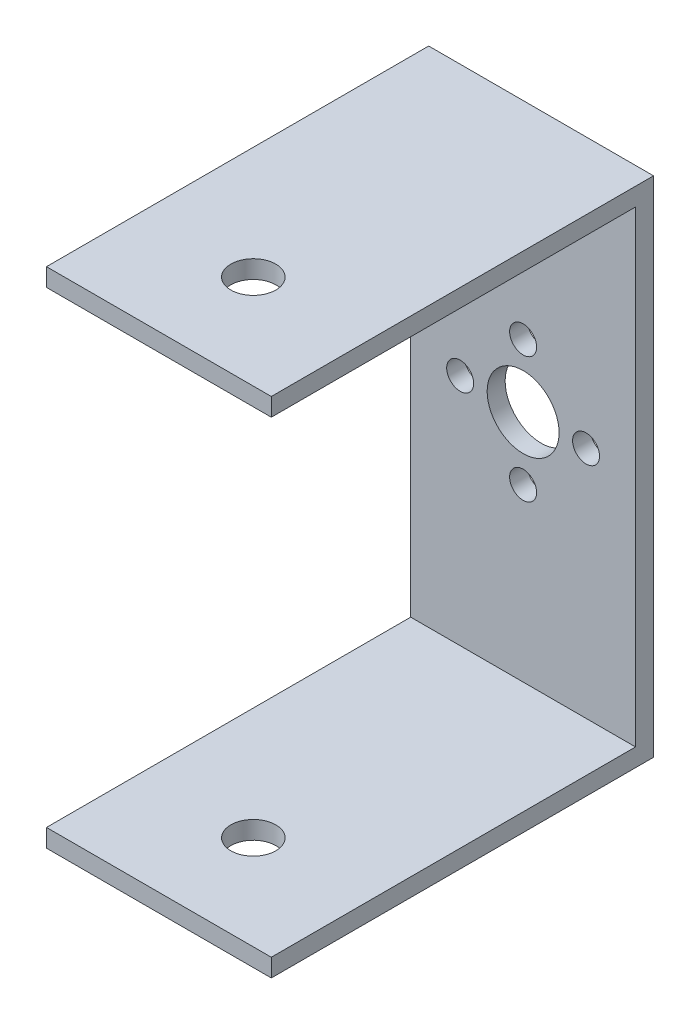
SolidWorks part; units mm, degrees
ref_plane "Front Plane" through (0, 0, 0) normal (0, 0, 1) x (1, 0, 0)
ref_plane "Top Plane" through (0, 0, 0) normal (0, 1, 0) x (1, 0, 0)
ref_plane "Right Plane" through (0, 0, 0) normal (1, 0, 0) x (0, 0, -1)
sketch "Sketch1" plane through (0, 0, 0) normal (0, 0, 1) x (1, 0, 0)
  line L1 (-12.6748, 30.5029) -> (12.3252, 30.5029)
  line L2 (-12.6748, 30.5029) -> (-12.6748, -21.4971)
  line L3 (-12.6748, -21.4971) -> (12.3252, -21.4971)
  line L4 (12.3252, 30.5029) -> (12.3252, -21.4971)
  dimension "D1" = 25
  dimension "D2" = 52
extrude "Boss-Extrude1" add sketch "Sketch1" along normal blind 2
sketch "Sketch2" plane through (0, 30.5029, 0) normal (0, 1, 0) x (1, 0, 0)
  line L1 (-12.6748, 0) -> (12.3252, 0)
  line L2 (-12.6748, 0) -> (-12.6748, -42.5)
  line L3 (-12.6748, -42.5) -> (12.3252, -42.5)
  line L4 (12.3252, 0) -> (12.3252, -42.5)
  dimension "D1" = 25
  dimension "D2" = 42.5
extrude "Boss-Extrude2" add sketch "Sketch2" along normal blind 2
sketch "Sketch3" plane through (0, -21.4971, 0) normal (0, -1, 0) x (-1, 0, 0)
  line L1 (-12.3252, 0) -> (12.6748, 0)
  line L2 (-12.3252, 0) -> (-12.3252, -42.5)
  line L3 (-12.3252, -42.5) -> (12.6748, -42.5)
  line L4 (12.6748, 0) -> (12.6748, -42.5)
  dimension "D1" = 25
  dimension "D2" = 42.5
extrude "Boss-Extrude3" add sketch "Sketch3" along normal blind 2
sketch "Sketch4" plane through (0, 32.5029, 0) normal (0, 1, 0) x (1, 0, 0)
  line L0 (-12.6748, 0) -> (-12.6748, -42.5) construction
  line L1 (12.3252, 0) -> (-12.6748, 0) construction
  circle A0 centre (-0.1748, -32) radius 2.5
  dimension "D1" = 12.5
  dimension "D2" = 32
extrude "Cut-Extrude1" cut sketch "Sketch4" against normal blind 70
sketch "Sketch5" plane through (0, 0, 0) normal (0, 0, -1) x (-1, 0, 0)
  line L0 (12.6748, 32.5029) -> (12.6748, -23.4971) construction
  circle A0 centre (0.1748, 4.5029) radius 4
  dimension "D1" = 12.5
extrude "Cut-Extrude2" cut sketch "Sketch5" against normal blind 21
sketch "Sketch6" plane through (0, 0, 0) normal (0, 0, -1) x (-1, 0, 0)
  circle A0 centre (7.1748, 4.5029) radius 1.5
  circle A1 centre (0.1748, 4.5029) radius 4 construction
  circle A2 centre (0.1748, -2.4971) radius 1.5
  circle A3 centre (-6.8252, 4.5029) radius 1.5
  circle A4 centre (0.1748, 11.5029) radius 1.5
  point P13 (0.1748, 4.5029)
  dimension "D1" = 7
  dimension "D2" = 4
extrude "Cut-Extrude3" cut sketch "Sketch6" against normal blind 21
